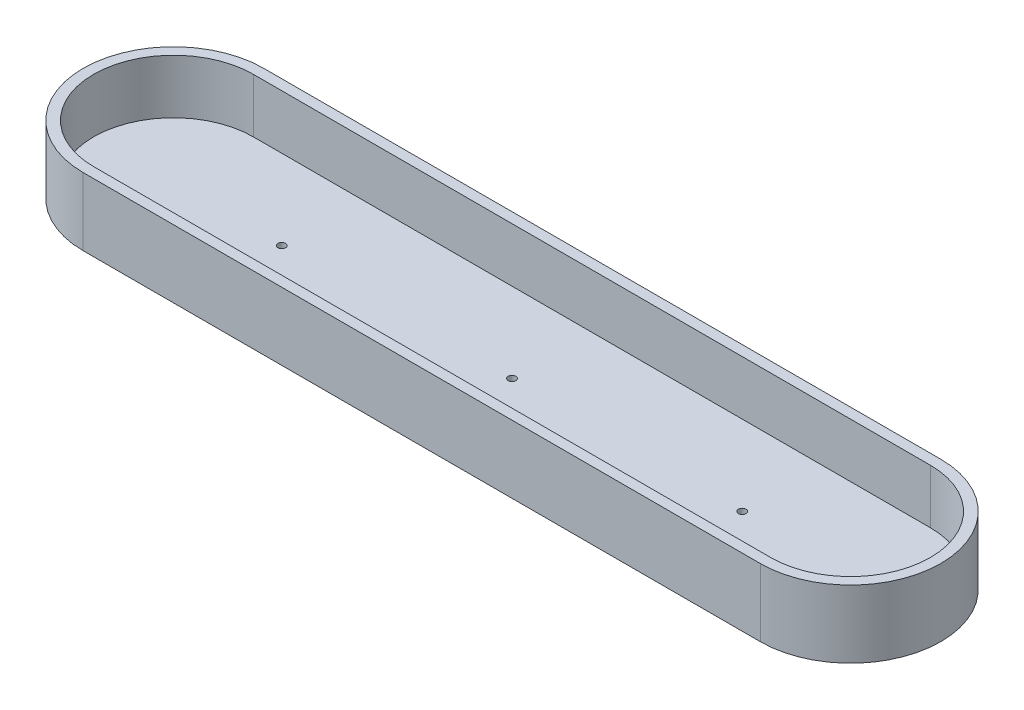
SolidWorks part; units mm, degrees
ref_plane "Front Plane" through (0, 0, 0) normal (0, 0, 1) x (1, 0, 0)
ref_plane "Top Plane" through (0, 0, 0) normal (0, 1, 0) x (1, 0, 0)
ref_plane "Right Plane" through (0, 0, 0) normal (1, 0, 0) x (0, 0, -1)
sketch "Sketch1" plane through (0, 0, 0) normal (0, 1, 0) x (1, 0, 0)
  line L0 (-95.25, 0) -> (95.25, 0) construction
  line L1 (0, -55.9739) -> (0, 55.9739) construction
  line L2 (-95.25, 22.479) -> (95.25, 22.479)
  line L3 (-95.25, -22.479) -> (95.25, -22.479)
  arc A0 (-95.25, 22.479) -> (-95.25, -22.479) centre (-95.25, 0) ccw
  arc A1 (95.25, 22.479) -> (95.25, -22.479) centre (95.25, 0) cw
  point P4 (0, 0)
  point P10 (0, 0)
  dimension "D2" = 44.958
  dimension "D1" = 190.5
extrude "MainBlock" add sketch "Sketch1" along normal blind 3.81
sketch "Sketch2" plane through (0, 0, 0) normal (0, -1, 0) x (1, 0, 0)
  line L0 (0, 0) -> (0, 50000) construction
  line L1 (-95.25, 25.4) -> (95.25, 25.4)
  line L2 (-95.25, -22.479) -> (95.25, -22.479)
  line L3 (95.25, 22.479) -> (-95.25, 22.479)
  line L5 (95.25, 22.479) -> (-95.25, 22.479)
  line L6 (-95.25, 0) -> (49904.75, 0) construction
  line L7 (95.25, -22.479) -> (-95.25, -22.479)
  line L8 (-95.25, -25.4) -> (95.25, -25.4)
  arc A0 (-95.25, 25.4) -> (-95.25, -25.4) centre (-95.25, 0) ccw
  arc A1 (95.25, 22.479) -> (95.25, -22.479) centre (95.25, 0) cw
  arc A2 (-95.25, 22.479) -> (-95.25, -22.479) centre (-95.25, 0) ccw
  arc A3 (95.25, -22.479) -> (95.25, 22.479) centre (95.25, 0) ccw
  arc A4 (-95.25, 22.479) -> (-95.25, -22.479) centre (-95.25, 0) ccw
  arc A6 (95.25, 25.4) -> (95.25, -25.4) centre (95.25, 0) cw
  point P0 (0, 22.479)
  point P15 (0, 25.4)
  point P16 (0, -22.479)
  point P19 (0, -25.4)
  dimension "2.1" = 50.8
  dimension "D1" = 0
extrude "Boss-Extrude1" add sketch "Sketch2" against normal blind 19.05
sketch "Sketch3" plane through (0, 0, 0) normal (0, -1, 0) x (1, 0, 0)
  line L0 (0, 0) -> (50000, 0) construction
  line L1 (0, 0) -> (0, 50000) construction
  circle A1 centre (0, 0) radius 1.0795
  circle A8 centre (-64.77, 0) radius 1.0795
  circle A9 centre (64.77, 0) radius 1.0795
  arc A10 (95.25, -25.4) -> (95.25, 25.4) centre (95.25, 0) ccw construction
  arc A11 (-95.25, 25.4) -> (-95.25, -25.4) centre (-95.25, 0) ccw construction
  arc A12 (95.25, -25.4) -> (95.25, 25.4) centre (95.25, 0) ccw construction
  arc A13 (-95.25, 25.4) -> (-95.25, -25.4) centre (-95.25, 0) ccw construction
  dimension "0.085" = 2.159
  dimension "D2" = 2.159
  dimension "D3" = 2.159
  dimension "D4" = 30.48
  dimension "D5" = 30.48
extrude "Cut-Extrude1" cut sketch "Sketch3" against normal through all
equation "\"D2@Sketch3\"=\"0.085@Sketch3\""
equation "\"D3@Sketch3\"=\"0.085@Sketch3\""
